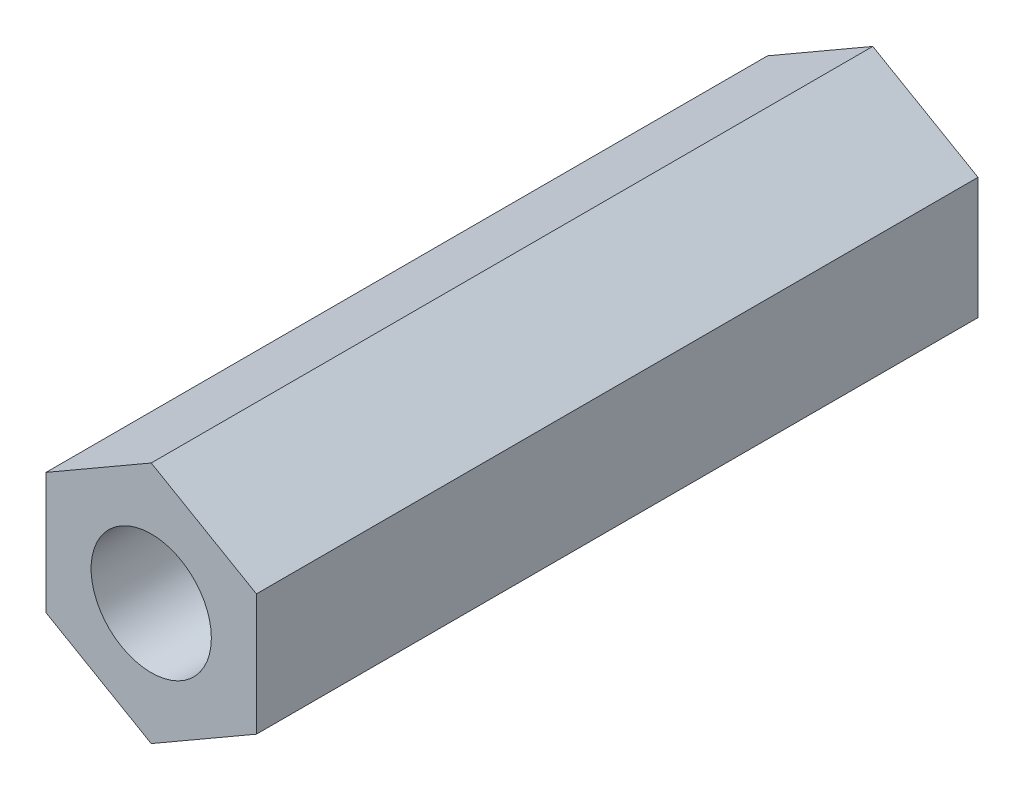
SolidWorks part; units mm, degrees
ref_plane "Piano frontale" through (0, 0, 0) normal (0, 0, 1) x (1, 0, 0)
ref_plane "Piano superiore" through (0, 0, 0) normal (0, 1, 0) x (1, 0, 0)
ref_plane "Piano destro" through (0, 0, 0) normal (1, 0, 0) x (0, 0, -1)
sketch "Schizzo1" plane through (0, 0, 0) normal (0, 0, 1) x (1, 0, 0)
  line L1 (0, 4.0415) -> (-3.5, 2.0207)
  line L2 (-3.5, 2.0207) -> (-3.5, -2.0207)
  line L3 (-3.5, -2.0207) -> (0, -4.0415)
  line L4 (0, -4.0415) -> (3.5, -2.0207)
  line L5 (3.5, -2.0207) -> (3.5, 2.0207)
  line L6 (3.5, 2.0207) -> (0, 4.0415)
  circle A0 centre (0, 0) radius 3.5 construction
  dimension "D1" = 7
extrude "Estrusione-Estrusione1" add sketch "Schizzo1" along normal blind 24
sketch "Schizzo2" plane through (0, 0, 24) normal (0, 0, 1) x (1, 0, 0)
  circle A0 centre (0, 0) radius 2
  dimension "D1" = 4
extrude "Taglio-Estrusione1" cut sketch "Schizzo2" against normal through all
